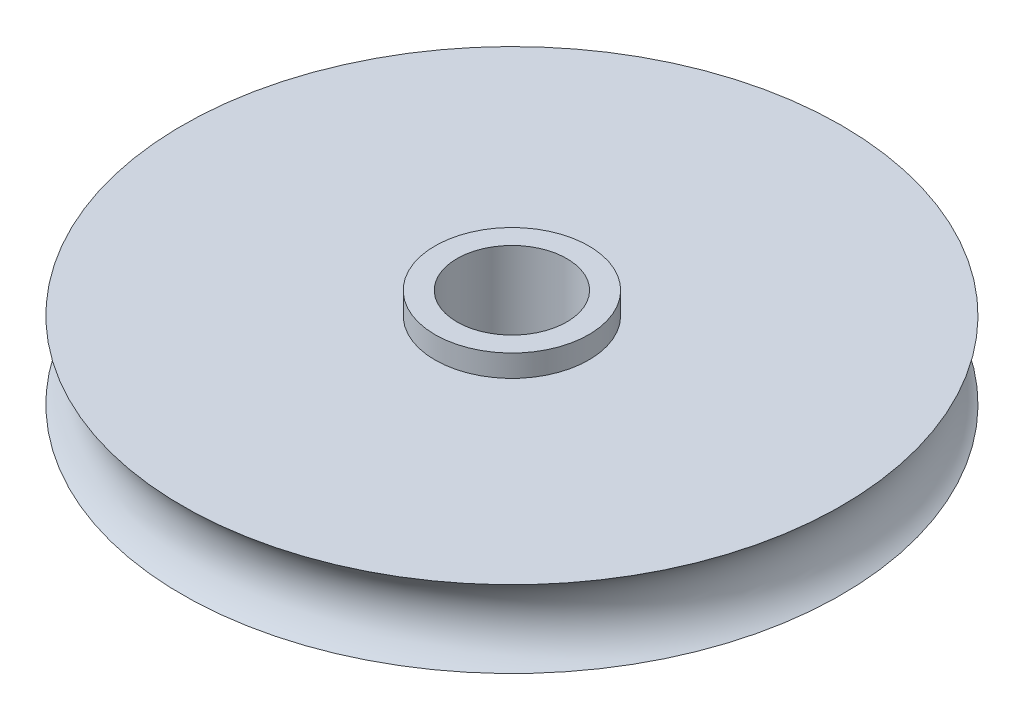
SolidWorks part; units mm, degrees
ref_plane "Front Plane" through (0, 0, 0) normal (0, 0, 1) x (1, 0, 0)
ref_plane "Top Plane" through (0, 0, 0) normal (0, 1, 0) x (1, 0, 0)
ref_plane "Right Plane" through (0, 0, 0) normal (1, 0, 0) x (0, 0, -1)
sketch "Sketch1" plane through (0, 0, 0) normal (0, 1, 0) x (1, 0, 0)
  circle A0 centre (0, 0) radius 15
  dimension "D1" = 30
extrude "Boss-Extrude1" add sketch "Sketch1" along normal blind 3.5
sketch "Sketch2" plane through (0, 0, 0) normal (1, 0, 0) x (0, 0, -1)
  line L0 (-15, 3.5) -> (-15, 0) construction
  line L1 (0, 0) -> (0, 10) construction
  circle A0 centre (-16.2, 1.75) radius 2.1219
  dimension "D1" = 1.2
revolve "Cut-Revolve1" cut sketch "Sketch2" angle 360 about L1
sketch "Sketch4" plane through (0, 0, 0) normal (0, -1, 0) x (1, 0, 0)
  circle A0 centre (0, 0) radius 3.5
  dimension "D1" = 7
extrude "Boss-Extrude2" add sketch "Sketch4" along normal blind 1
sketch "Sketch5" plane through (0, 3.5, 0) normal (0, 1, 0) x (1, 0, 0)
  circle A0 centre (0, 0) radius 3.5
  dimension "D1" = 7
extrude "Boss-Extrude3" add sketch "Sketch5" along normal blind 1
sketch "Sketch3" plane through (0, 3.5, 0) normal (0, 1, 0) x (1, 0, 0)
  circle A0 centre (0, 0) radius 2.5
  dimension "D1" = 5
extrude "Cut-Extrude1" cut sketch "Sketch3" against normal through all and the other way through all
equation "\"pulleyED\"=30"
equation "\"D1@Sketch1\"=\"pulleyED\""
equation "\"pulleyWidth\"=3.5"
equation "\"D1@Boss-Extrude1\"=\"pulleyWidth\""
equation "\"pulleyHoleDiameter\"=5"
equation "\"D1@Sketch3\"=\"pulleyHoleDiameter\""
equation "\"D1@Sketch4\"=\"pulleyHoleDiameter\" +2"
equation "\"D1@Sketch5\"=\"pulleyHoleDiameter\"+2"
